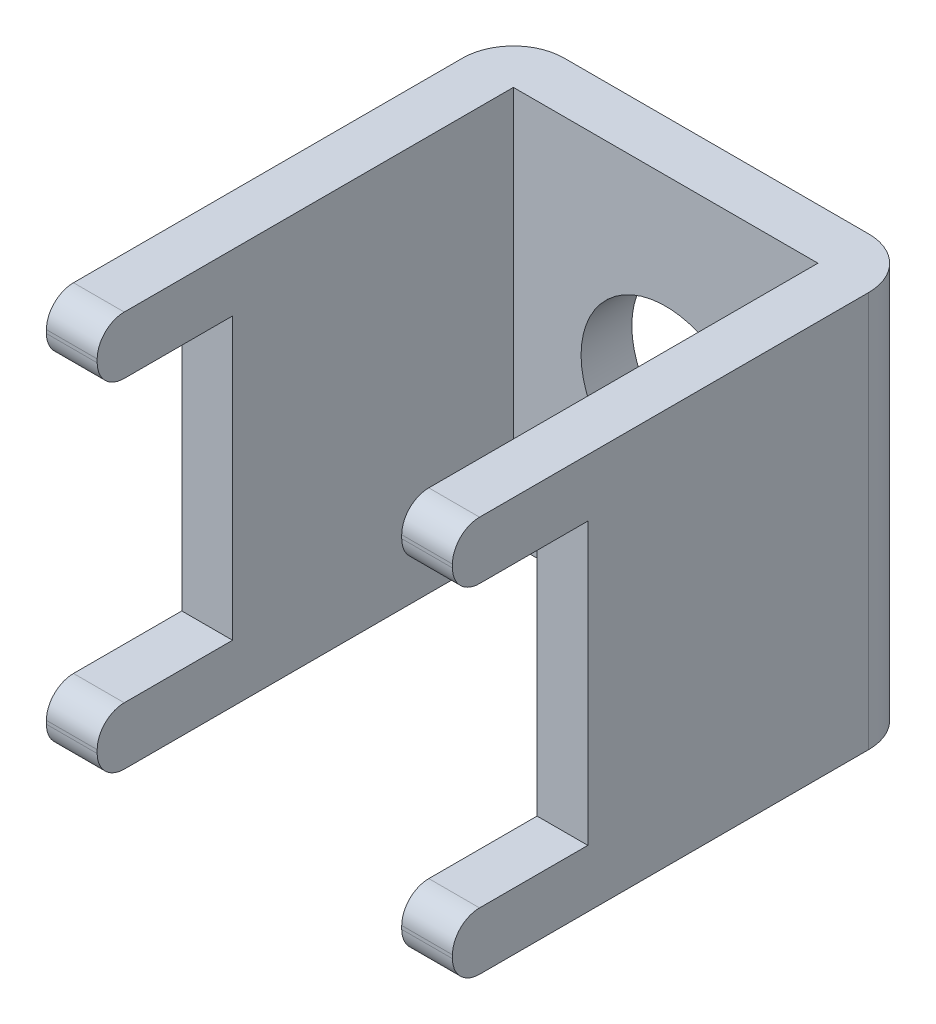
SolidWorks part; units mm, degrees
ref_plane "Front Plane" through (0, 0, 0) normal (0, 0, 1) x (1, 0, 0)
ref_plane "Top Plane" through (0, 0, 0) normal (0, 1, 0) x (1, 0, 0)
ref_plane "Right Plane" through (0, 0, 0) normal (1, 0, 0) x (0, 0, -1)
sketch "Sketch1" plane through (0, 0, 0) normal (0, 1, 0) x (1, 0, 0)
  line L0 (0, 0) -> (-1.5, 0)
  line L1 (-1.5, 0) -> (-1.5, 12.3)
  line L2 (0, 13.8) -> (9, 13.8)
  line L3 (10.5, 12.3) -> (10.5, 0)
  line L4 (10.5, 0) -> (9, 0)
  line L5 (9, 0) -> (9, 12.3)
  line L6 (9, 12.3) -> (0, 12.3)
  line L7 (0, 12.3) -> (0, 0)
  arc A0 (9, 13.8) -> (10.5, 12.3) centre (9, 12.3) cw
  arc A1 (-1.5, 12.3) -> (0, 13.8) centre (0, 12.3) cw
  dimension "D5" = 1.5
  dimension "D1" = 1.5
  dimension "D2" = 1.5
  dimension "D3" = 12
  dimension "D4" = 13.8
extrude "Boss-Extrude1" add sketch "Sketch1" along normal blind 11.7
sketch "Sketch2" plane through (10.5, 0, 0) normal (1, 0, 0) x (0, 0, -1)
  line L0 (0, 11.7) -> (0, 0) construction
  line L1 (0, 10) -> (4, 10)
  line L2 (0, 10) -> (0, 1.7)
  line L3 (0, 1.7) -> (4, 1.7)
  line L4 (4, 10) -> (4, 1.7)
  line L5 (0, 11.7) -> (12.3, 11.7) construction
  line L6 (0, 0) -> (12.3, 0) construction
  point P8 (2, 1.7)
  dimension "D1" = 1.7
  dimension "D2" = 1.7
  dimension "D3" = 4
extrude "Cut-Extrude2" cut sketch "Sketch2" against normal up to surface (12 mm away) up to face at (-1.5, 5.85, -6.15)
fillet "Fillet1" radius 0.8 8 edges at (9.75, 10, 0) (9.75, 11.7, 0) (9.75, 0, 0) (9.75, 1.7, 0) (-0.75, 10, 0) (-0.75, 11.7, 0) (-0.75, 0, 0) (-0.75, 1.7, 0)
sketch "Sketch3" plane through (0, 0, -13.8) normal (0, 0, -1) x (-1, 0, 0)
  line L0 (-9, 11.7) -> (0, 0) construction
  circle A0 centre (-4.5, 5.85) radius 2.5
  dimension "D1" = 5
extrude "Cut-Extrude3" cut sketch "Sketch3" against normal up to surface (1.5 mm away) up to face at (4.5, 5.85, -12.3)
